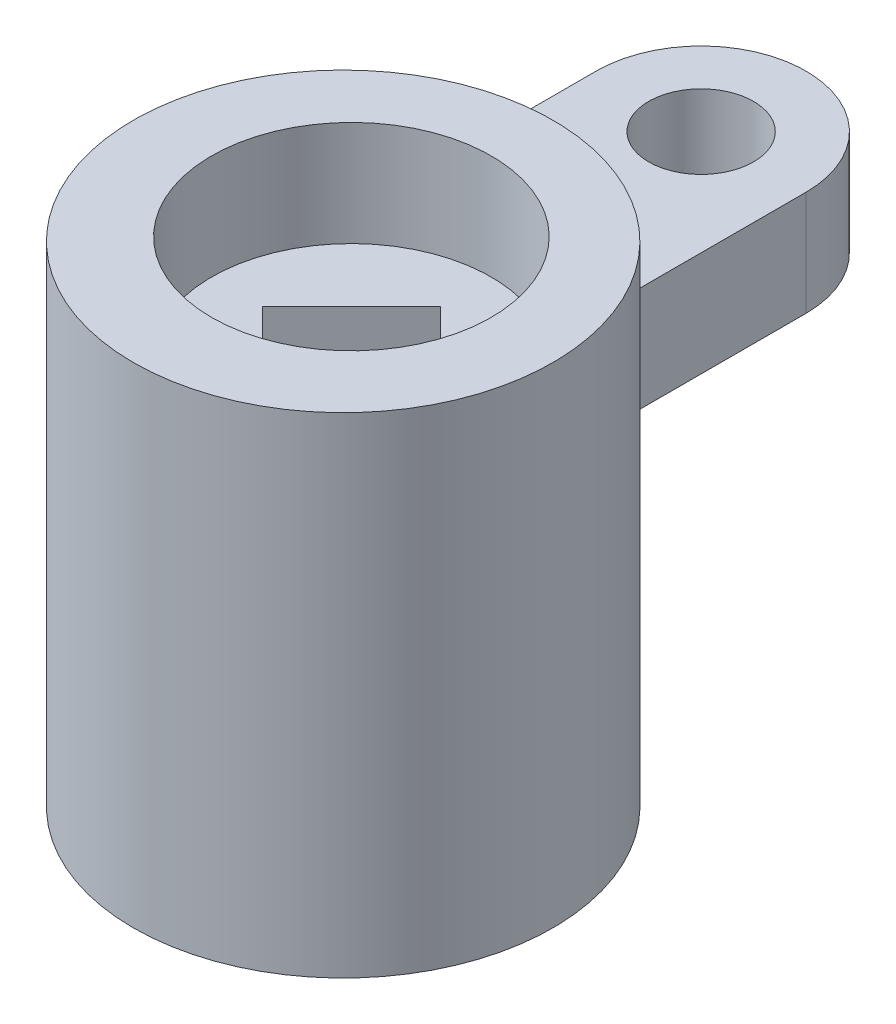
SolidWorks part; units mm, degrees
ref_plane "前视基准面" through (0, 0, 0) normal (0, 0, 1) x (1, 0, 0)
ref_plane "上视基准面" through (0, 0, 0) normal (0, 1, 0) x (1, 0, 0)
ref_plane "右视基准面" through (0, 0, 0) normal (1, 0, 0) x (0, 0, -1)
other "Configuration Table"
sketch "草图2" plane through (0, 0, 0) normal (0, 1, 0) x (1, 0, 0)
  circle A0 centre (0, -1.1735) radius 30
extrude "凸台-拉伸1" add sketch "草图2" along normal blind 70 contours A0
sketch "草图3" plane through (0, 70, 0) normal (0, 1, 0) x (1, 0, 0)
  circle A0 centre (0, 0) radius 20
extrude "切除-拉伸2" cut sketch "草图3" against normal blind 15
sketch "草图5" plane through (0, 0, 0) normal (0, -1, 0) x (1, 0, 0)
  line L0 (0, 9.8709) -> (0, -15.871) construction
  line L1 (0, 12.7279) -> (12.7279, 0)
  line L2 (33, 0) -> (-33, 0) construction
  line L3 (12.7279, 0) -> (0, -12.7279)
  line L4 (0, -12.7279) -> (-12.7279, 0)
  line L5 (-12.7279, 0) -> (0, 12.7279)
  dimension "D1" = 18
  dimension "D2" = 45
  dimension "D3" = 4
extrude "切除-拉伸3" cut sketch "草图5" against normal blind 55 contours L1 L3 L4 L5
sketch "草图6" plane through (0, 0, 0) normal (0, 1, 0) x (1, 0, 0)
  line L0 (0, 0) -> (0, 50) construction
  line L1 (-15, 50) -> (-15, 24.8073)
  line L2 (15, 50) -> (15, 24.8073)
  arc A1 (15, 50) -> (-15, 50) centre (0, 50) ccw
  circle A2 centre (0, -1.1735) radius 30 construction
  circle A4 centre (0, -1.1735) radius 30
  arc A5 (15, 24.8073) -> (-15, 24.8073) centre (0, -1.1735) ccw
  dimension "D1" = 0
extrude "凸台-拉伸2" add sketch "草图6" along normal blind 15 from offset 43 contours A1 L1 A5 L2
sketch "草图7" plane through (0, 58, 0) normal (0, 1, 0) x (1, 0, 0)
  circle A0 centre (0, 50) radius 7.5
  arc A1 (15, 50) -> (-15, 50) centre (0, 50) ccw construction
extrude "切除-拉伸4" cut sketch "草图7" against normal blind 15
